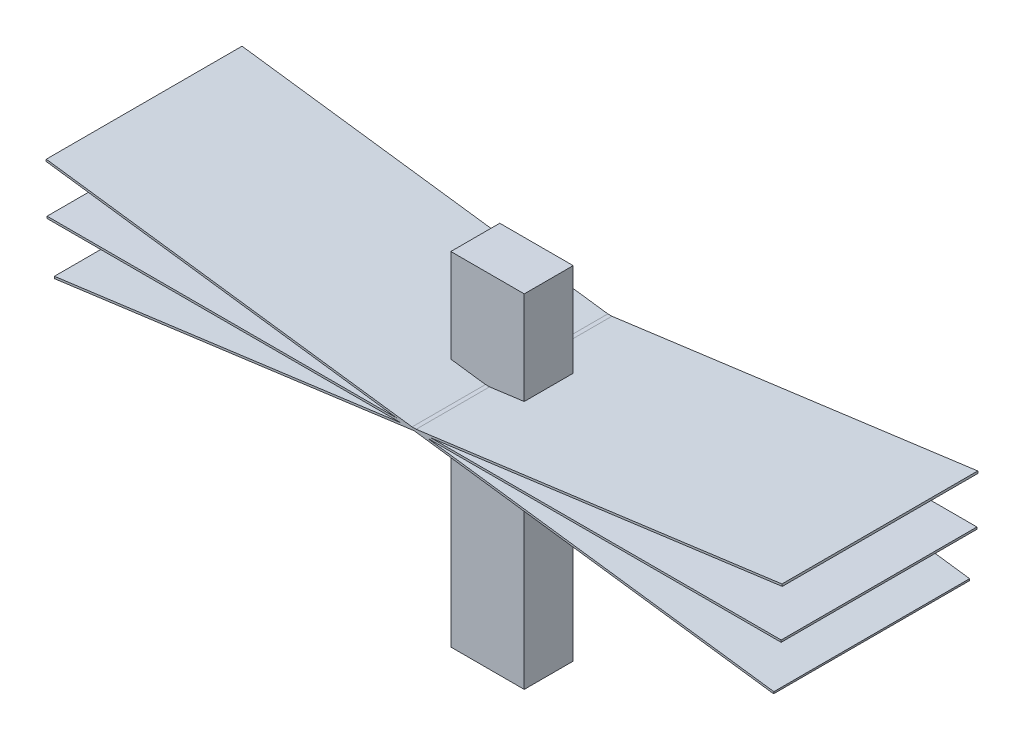
SolidWorks part; units mm, degrees
material "Plain Carbon Steel"
ref_plane "Front Plane" through (0, 0, 0) normal (0, 0, 1) x (1, 0, 0)
ref_plane "Top Plane" through (0, 0, 0) normal (0, 1, 0) x (1, 0, 0)
ref_plane "Right Plane" through (0, 0, 0) normal (1, 0, 0) x (0, 0, -1)
sketch "Sketch1" plane through (0, 0, 0) normal (0, 0, 1) x (1, 0, 0)
  line L0 (55, 0) -> (-55, 0) construction
  line L1 (-228.6, 0) -> (228.6, 0)
  line L2 (-228.6, 0) -> (-228.6, 2133.6)
  line L3 (-228.6, 2133.6) -> (228.6, 2133.6)
  line L4 (228.6, 0) -> (228.6, 2133.6)
  dimension "D1" = 2133.6
  dimension "D2" = 457.2
extrude "Boss-Extrude1" add sketch "Sketch1" along normal mid plane 304.8
sketch "Sketch2" plane through (0, 0, 0) normal (0, 0, 1) x (1, 0, 0)
  line L0 (0, 1524) -> (0, 1511.3) construction
  line L1 (-2286, 1524) -> (2286, 1524)
  line L2 (-2286, 1524) -> (-2286, 1511.3)
  line L3 (-2286, 1511.3) -> (2286, 1511.3)
  line L4 (2286, 1524) -> (2286, 1511.3)
  line L5 (0, -167.64) -> (0, 167.64) construction
  line L7 (167.64, 0) -> (-167.64, 0) construction
  line L8 (0, 1524) -> (0, 1714.5) construction
  line L9 (0, 1714.5) -> (25.2598, 1525.6821) construction
  line L10 (-2240.5547, 1222.5642) -> (2291.0744, 1828.8)
  line L11 (-2240.5547, 1222.5642) -> (-2238.8707, 1209.9764)
  line L12 (2291.0744, 1828.8) -> (2292.7584, 1816.2121)
  line L13 (-2238.8707, 1209.9764) -> (2292.7584, 1816.2121)
  dimension "D1" = 12.7
  dimension "D2" = 4572
  dimension "D3" = 1524
  dimension "D4" = 190.5
  dimension "D5" = 1828.8
  dimension "D6" = 1222.5642
extrude "Boss-Extrude2" add sketch "Sketch2" along normal mid plane 1219.2 contours L3 L10 L1 L2 | L11 L13 L3 L10 | L3 L13 L1 L10 | L1 L13 L12 L10 | L13 L3 L4 L1
mirror "Mirror1" about plane through (0, 0, 0) normal (1, 0, 0) of "Boss-Extrude2"
